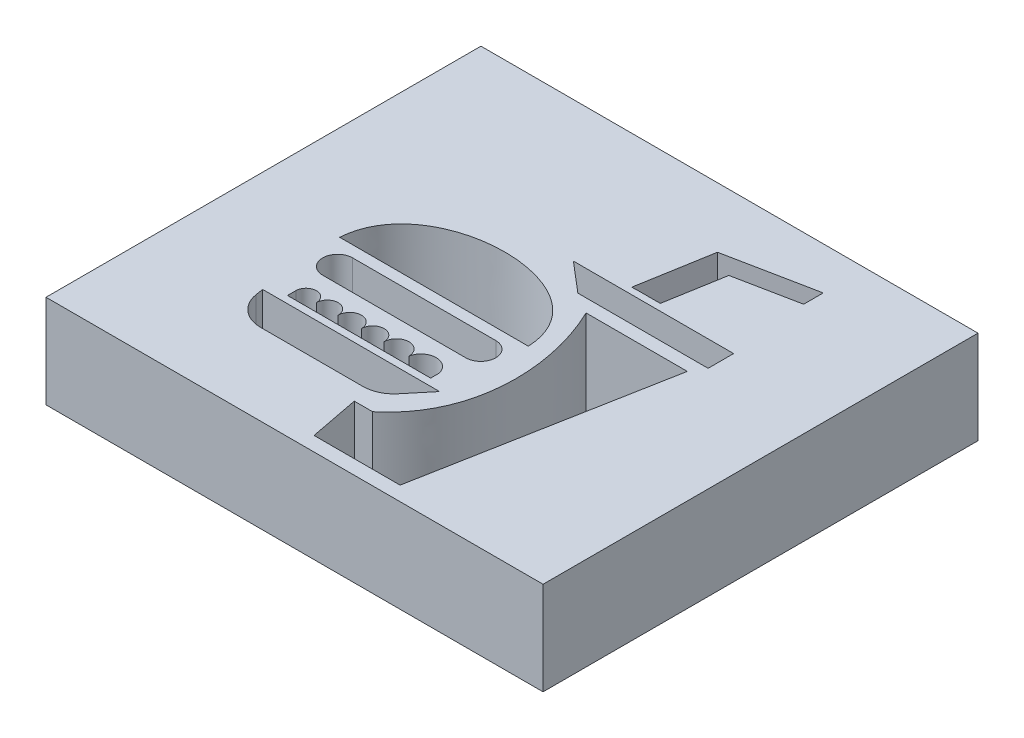
SolidWorks part; units mm, degrees
ref_plane "Front Plane" through (0, 0, 0) normal (0, 0, 1) x (1, 0, 0)
ref_plane "Top Plane" through (0, 0, 0) normal (0, 1, 0) x (1, 0, 0)
ref_plane "Right Plane" through (0, 0, 0) normal (1, 0, 0) x (0, 0, -1)
sketch "Sketch1" plane through (0, 0, 0) normal (0, 1, 0) x (1, 0, 0)
  line L1 (-42.8025, 22.3185) -> (-26.8025, 22.3185)
  line L2 (-42.8025, 22.3185) -> (-42.8025, 8.3185)
  line L3 (-42.8025, 8.3185) -> (-26.8025, 8.3185)
  line L4 (-26.8025, 22.3185) -> (-26.8025, 8.3185)
  line L36 (-39.7478, 14.717) -> (-33.6758, 14.717)
  line L37 (-38.9659, 13.8686) -> (-34.3578, 13.8686) construction
  line L38 (-38.9659, 14.351) -> (-34.3578, 14.351)
  line L39 (-38.9659, 13.3862) -> (-34.3578, 13.3862)
  line L40 (-39.5338, 12.0242) -> (-33.839, 12.0242)
  line L41 (-38.9659, 12.5211) -> (-38.9659, 12.2549)
  line L42 (-38.9659, 12.2549) -> (-34.3578, 12.2549)
  line L43 (-34.3578, 12.2549) -> (-34.3578, 12.5211)
  line L44 (-33.839, 12.0242) -> (-34.4435, 11.2945)
  line L45 (-35.2136, 10.9326) -> (-38.5074, 10.9326)
  line L46 (-39.4955, 11.7784) -> (-39.5338, 12.0242)
  line L47 (-34.9454, 10.3845) -> (-34.6357, 8.78)
  line L48 (-34.6357, 8.78) -> (-31.8659, 8.78)
  line L49 (-31.8659, 8.78) -> (-30.4142, 16.5735)
  line L50 (-30.4142, 16.5735) -> (-33.6758, 16.5735)
  line L51 (-34.3578, 10.3845) -> (-34.9454, 10.3845)
  line L52 (-34.3578, 16.9937) -> (-30.1659, 16.9937)
  line L53 (-30.1659, 16.9937) -> (-30.1659, 17.8151)
  line L54 (-30.1659, 17.8151) -> (-35.3227, 17.8151)
  line L55 (-35.3227, 17.8151) -> (-34.3578, 16.9937)
  line L56 (-33.473, 18.0331) -> (-32.7443, 18.0331)
  line L57 (-30.4142, 20.3174) -> (-30.4142, 20.9478)
  line L58 (-32.7443, 18.0331) -> (-32.4199, 19.9163)
  line L59 (-32.4199, 19.9163) -> (-30.4142, 20.3174)
  line L60 (-30.4142, 20.9478) -> (-33.2508, 20.3805)
  line L61 (-33.2508, 20.3805) -> (-33.6552, 18.0331)
  arc A1 (-38.9659, 14.351) -> (-38.9659, 13.3862) centre (-38.9659, 13.8686) ccw
  arc A2 (-34.3578, 13.3862) -> (-34.3578, 14.351) centre (-34.3578, 13.8686) ccw
  arc A3 (-38.9659, 12.5211) -> (-38.3005, 12.5211) centre (-38.6332, 12.5211) cw
  arc A4 (-38.3005, 12.5211) -> (-37.6018, 12.5211) centre (-37.9511, 12.5211) cw
  arc A5 (-37.6018, 12.5211) -> (-36.8532, 12.5211) centre (-37.2275, 12.5211) cw
  arc A6 (-36.8532, 12.5211) -> (-36.1212, 12.5211) centre (-36.4872, 12.5211) cw
  arc A7 (-36.1212, 12.5211) -> (-35.3227, 12.5211) centre (-35.7219, 12.5211) cw
  arc A9 (-35.3227, 12.5211) -> (-34.3578, 12.5211) centre (-34.8402, 12.4244) cw
  arc A10 (-34.4435, 11.2945) -> (-35.2136, 10.9326) centre (-35.2136, 11.9326) cw
  arc A11 (-38.5074, 10.9326) -> (-39.4955, 11.7784) centre (-38.5074, 11.9326) cw
  arc A12 (-33.6552, 18.0331) -> (-33.473, 18.0331) centre (-33.5641, 18.5617) ccw
  spline S0 degree 3 poles (-39.7478, 14.717) (-39.5611, 17.7011) (-33.7975, 17.7312) (-33.6758, 14.717) knots 0 0 0 0 1 1 1 1
  spline S1 degree 3 poles (-33.6758, 16.5735) (-32.7359, 14.6617) (-32.5253, 11.8814) (-34.3578, 10.3845) knots 0 0 0 0 1 1 1 1
  point P10 (-36.6619, 13.8686)
  point P58 (-38.5074, 10.9326)
  dimension "D3" = 1
  dimension "D1" = 16
  dimension "D2" = 14
extrude "Boss-Extrude1" add sketch "Sketch1" along normal blind 3
